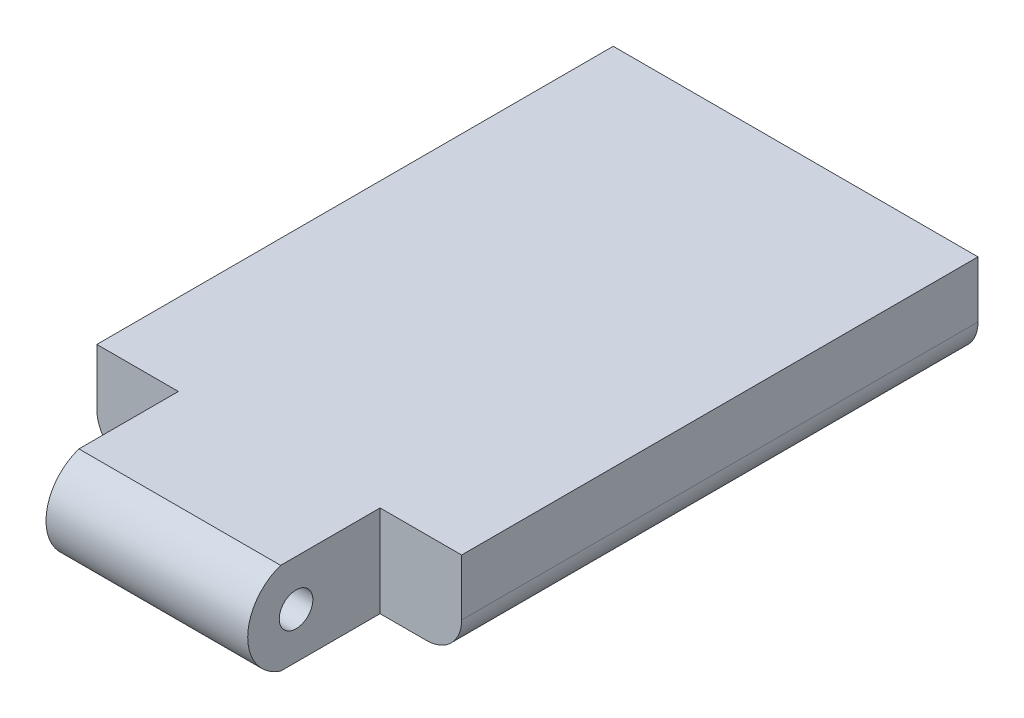
SolidWorks part; units mm, degrees
ref_plane "Front Plane" through (0, 0, 0) normal (0, 0, 1) x (1, 0, 0)
ref_plane "Top Plane" through (0, 0, 0) normal (0, 1, 0) x (1, 0, 0)
ref_plane "Right Plane" through (0, 0, 0) normal (1, 0, 0) x (0, 0, -1)
sketch "Sketch1" plane through (0, 0, 0) normal (0, 0, 1) x (1, 0, 0)
  line L0 (-17.5, 16.5) -> (-22, 16.5)
  line L1 (-22, 16.5) -> (-22, 9.5)
  line L2 (-17.5, 5) -> (17.5, 5)
  line L3 (22, 9.5) -> (22, 16.5)
  line L4 (22, 16.5) -> (-17.5, 16.5)
  arc A0 (-22, 9.5) -> (-17.5, 5) centre (-17.5, 9.5) ccw
  arc A1 (17.5, 5) -> (22, 9.5) centre (17.5, 9.5) ccw
extrude "Boss-Extrude1" add sketch "Sketch1" against normal up to vertex from offset 15
sketch "Sketch2" plane through (0, 0, 15) normal (0, 0, 1) x (1, 0, 0)
  line L0 (22, 16.5) -> (-22, 16.5) construction
  line L1 (12, 16.5) -> (-12, 16.5)
  line L2 (12, 16.5) -> (12, 5)
  line L3 (12, 5) -> (-12, 5)
  line L4 (-12, 16.5) -> (-12, 5)
  line L5 (-17.5, 5) -> (17.5, 5) construction
  line L6 (-22, 16.5) -> (-22, 9.5) construction
  line L7 (22, 9.5) -> (22, 16.5) construction
  dimension "D1" = 10
  dimension "D2" = 10
extrude "Boss-Extrude2" add sketch "Sketch2" along normal blind 10
sketch "Sketch3" plane through (12, 0, 0) normal (1, 0, 0) x (0, 0, -1)
  line L0 (-25, 5) -> (-25, 16.5) construction
  line L1 (-25, 16.5) -> (-15, 16.5) construction
  line L2 (-25, 5) -> (-25, 16.5)
  arc A0 (-25, 5) -> (-25, 16.5) centre (-25, 10.75) cw
  point P8 (-25, 16.1875)
extrude "Boss-Extrude3" add sketch "Sketch3" against normal up to vertex
sketch "Sketch4" plane through (12, 0, 0) normal (1, 0, 0) x (0, 0, -1)
  circle A0 centre (-25, 10.75) radius 2
  dimension "D1" = 4
extrude "Cut-Extrude1" cut sketch "Sketch4" against normal up to vertex (24 mm away)
sketch "Sketch5" plane through (0, 0, -46.4391) normal (0, 0, -1) x (-1, 0, 0)
  line L4 (22, 16.5) -> (-22, 16.5)
  line L5 (-22, 16.5) -> (-22, 9.5)
  line L6 (-17.5, 5) -> (17.5, 5)
  line L7 (22, 9.5) -> (22, 16.5)
  line L8 (22, 16.5) -> (-22, 16.5)
  line L9 (-22, 16.5) -> (-22, 9.5)
  line L10 (-17.5, 5) -> (17.5, 5)
  line L11 (22, 9.5) -> (22, 16.5)
  line L16 (21.7, 16.2) -> (-21.7, 16.2)
  line L17 (-21.7, 16.2) -> (-21.7, 9.5)
  line L18 (-17.5, 5.3) -> (17.5, 5.3)
  line L19 (21.7, 9.5) -> (21.7, 16.2)
  line L20 (21.7, 16.2) -> (-21.7, 16.2)
  line L21 (-21.7, 16.2) -> (-21.7, 9.5)
  line L22 (-17.5, 5.3) -> (17.5, 5.3)
  line L23 (21.7, 9.5) -> (21.7, 16.2)
  arc A2 (-22, 9.5) -> (-17.5, 5) centre (-17.5, 9.5) ccw
  arc A3 (17.5, 5) -> (22, 9.5) centre (17.5, 9.5) ccw
  arc A4 (-22, 9.5) -> (-17.5, 5) centre (-17.5, 9.5) ccw
  arc A5 (17.5, 5) -> (22, 9.5) centre (17.5, 9.5) ccw
  arc A8 (-21.7, 9.5) -> (-17.5, 5.3) centre (-17.5, 9.5) ccw
  arc A9 (17.5, 5.3) -> (21.7, 9.5) centre (17.5, 9.5) ccw
  arc A10 (-21.7, 9.5) -> (-17.5, 5.3) centre (-17.5, 9.5) ccw
  arc A11 (17.5, 5.3) -> (21.7, 9.5) centre (17.5, 9.5) ccw
  dimension "D1" = 0
  dimension "D2" = 0.3
extrude "Cut-Extrude2" cut sketch "Sketch5" against normal up to vertex
